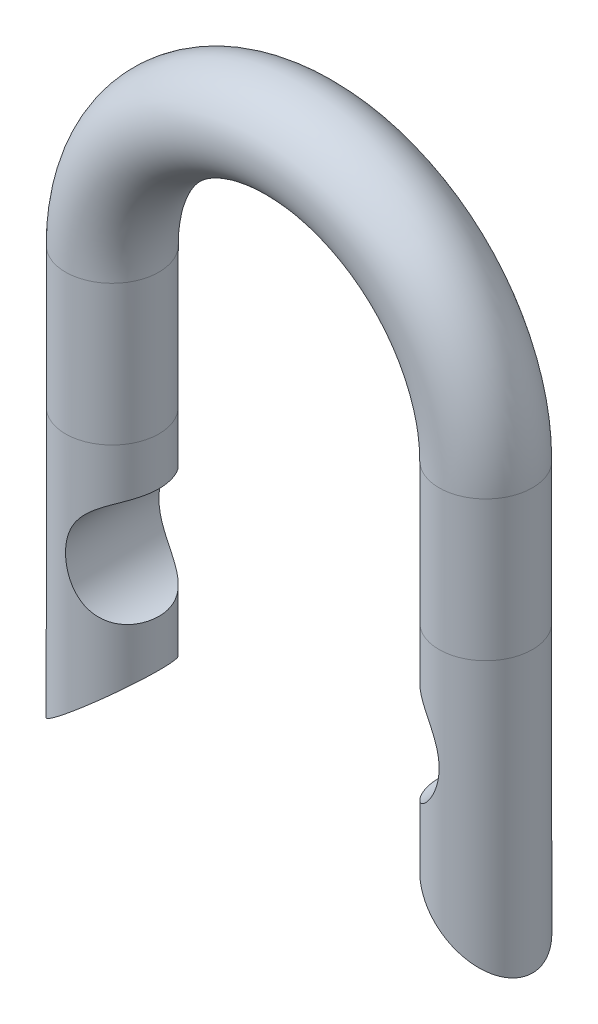
SolidWorks part; units mm, degrees
material "EN 1.5510+H Boron Steel Hardened"
ref_plane "Front Plane" through (0, 0, 0) normal (0, 0, 1) x (1, 0, 0)
ref_plane "Top Plane" through (0, 0, 0) normal (0, 1, 0) x (1, 0, 0)
ref_plane "Right Plane" through (0, 0, 0) normal (1, 0, 0) x (0, 0, -1)
sketch "Sketch2" plane through (0, 0, 0) normal (0, 0, 1) x (1, 0, 0)
  line L0 (0, 0) -> (0, 15)
  line L1 (40, 15) -> (40, 0)
  line L2 (-8.7138, 35) -> (48.7138, 35) construction
  line L3 (40, 0) -> (40, -30)
  line L4 (0, 0) -> (0, -30)
  arc A0 (0, 15) -> (40, 15) centre (20, 15) cw
  point P8 (20, 35)
  point P9 (20, 35)
  dimension "D1" = 40
  dimension "D2" = 35
  dimension "D3" = 30
  dimension "D4" = 30
sweep "Sweep1" add path "Sketch2" circular profile diameter 10 parameters "D3"=10
sketch "Sketch14" plane through (0, 0, 0) normal (0, 0, 1) x (1, 0, 0)
  line L1 (5, 0) -> (35, 0) construction
  line L4 (6, -5) -> (34, -5) construction
  line L5 (20, 0) -> (20, -11) construction
  line L9 (0, -5) -> (0, -17) construction
  line L10 (6, -5) -> (34, -5)
  line L11 (34, -17) -> (6, -17)
  line L12 (0, -5) -> (0, -17) construction
  line L13 (18.2875, 0) -> (-18.2875, 0) construction
  line L14 (-5, 0) -> (5, 0) construction
  line L15 (0, 0) -> (0, -23.506) construction
  line L16 (0, -18.2875) -> (0, 18.2875) construction
  line L17 (9.1031, -5) -> (-9.1031, -5) construction
  line L18 (-9.1031, -17) -> (9.1031, -17) construction
  arc A0 (6, -5) -> (6, -17) centre (6, -11) ccw
  arc A1 (34, -5) -> (34, -17) centre (34, -11) cw
  dimension "D1" = 6
  dimension "D2" = 5
  dimension "D3" = 0
  dimension "D4" = 0
extrude "Cut-Extrude1" cut sketch "Sketch14" against normal through all both and the other way through all
sketch "Sketch15" plane through (0, 0, 0) normal (0, 0, 1) x (1, 0, 0)
  line L0 (20, 15) -> (20, 40) construction
  line L1 (5, 15) -> (35, 15) construction
  line L2 (20, 15) -> (20, 0) construction
  line L4 (18.2875, 0) -> (-18.2875, 0) construction
  arc A0 (45, 15) -> (-5, 15) centre (20, 15) ccw construction
sketch "Sketch22" plane through (0, 0, 0) normal (0, 0, 1) x (1, 0, 0)
  line L0 (-5, -30) -> (5, -21.9161)
  line L1 (5, -30) -> (5, -16.9161) construction
  line L2 (5, -21.9161) -> (5, -30)
  line L4 (5, -30) -> (-5, -30)
  line L5 (20, 15) -> (20, 0) construction
  line L6 (5, 15) -> (35, 15) construction
  line L7 (35, -30) -> (45, -30)
  line L8 (35, -21.9161) -> (35, -30)
  line L9 (45, -30) -> (35, -21.9161)
  dimension "D1" = 5
extrude "Cut-Extrude3" cut sketch "Sketch22" against normal through all both and the other way through all
sketch "Sketch23" plane through (0, 0, 0) normal (0, 0, 1) x (1, 0, 0)
  line L0 (-5, -30) -> (-5, -35) construction
  dimension "D1" = 5
